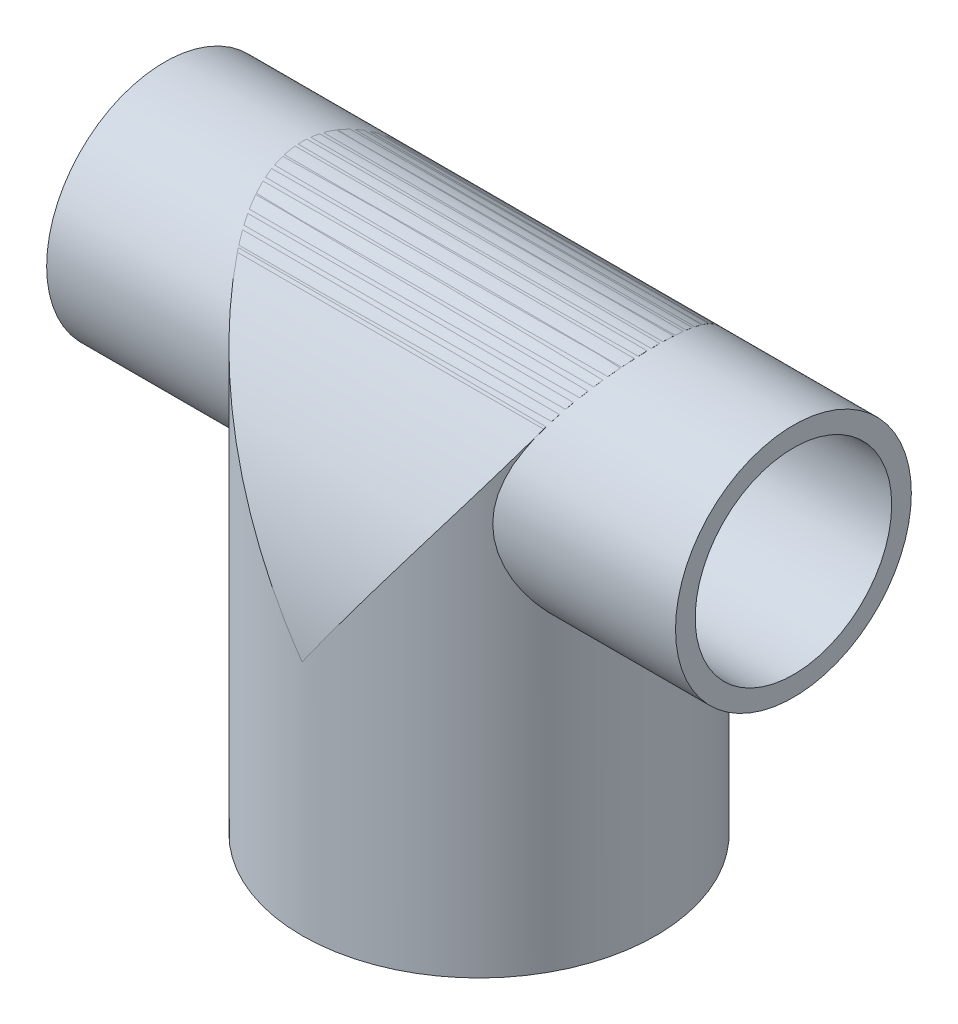
SolidWorks part; units mm, degrees
ref_plane "前视基准面" through (0, 0, 0) normal (0, 0, 1) x (1, 0, 0)
ref_plane "上视基准面" through (0, 0, 0) normal (0, 1, 0) x (1, 0, 0)
ref_plane "右视基准面" through (0, 0, 0) normal (1, 0, 0) x (0, 0, -1)
sketch "草图1" plane through (0, 0, 0) normal (1, 0, 0) x (0, 0, -1)
  circle A0 centre (0, 0) radius 6
  circle A1 centre (0, 0) radius 5
  dimension "D1" = 12
  dimension "D2" = 10
extrude "凸台-拉伸1" add sketch "草图1" along normal mid plane 32
ref_plane "基准面4" through (0, 6, 0) normal (0, 1, 0) x (1, 0, 0)
sketch "草图3" plane through (0, 6, 0) normal (0, 1, 0) x (1, 0, 0)
  circle A0 centre (0, 0) radius 9
  dimension "D1" = 18
extrude "凸台-拉伸2" add sketch "草图3" against normal blind 26 separate body
sketch "草图4" plane through (0, -20, 0) normal (0, -1, 0) x (-1, 0, 0)
  circle A0 centre (0, 0) radius 8
  dimension "D1" = 16
extrude "切除-拉伸1" cut sketch "草图4" against normal blind 14
sketch "草图6" plane through (0, 0, 0) normal (1, 0, 0) x (0, 0, -1)
  circle A0 centre (0, 0) radius 5
extrude "切除-拉伸2" cut sketch "草图6" against normal mid plane 25
sketch "草图7" plane through (0, 0, 0) normal (1, 0, 0) x (0, 0, -1)
  line L0 (9, 8) -> (9, -7.9373)
  line L1 (0, 0) -> (0, -9.5502) construction
  line L2 (-9, -7.9373) -> (-9, 8)
  line L6 (-9, 8) -> (9, 8)
  arc A0 (4.5, 3.9686) -> (9, -7.9373) centre (-9, -7.9373) cw
  circle A1 centre (0, 0) radius 6 construction
  arc A2 (-4.5, 3.9686) -> (-9, -7.9373) centre (9, -7.9373) ccw
  arc A3 (-4.5, 3.9686) -> (4.5, 3.9686) centre (0, 0) cw
  dimension "D2" = 18
  dimension "D1" = 8
  dimension "D3" = 9
extrude "切除-拉伸3" cut sketch "草图7" against normal mid plane 25
